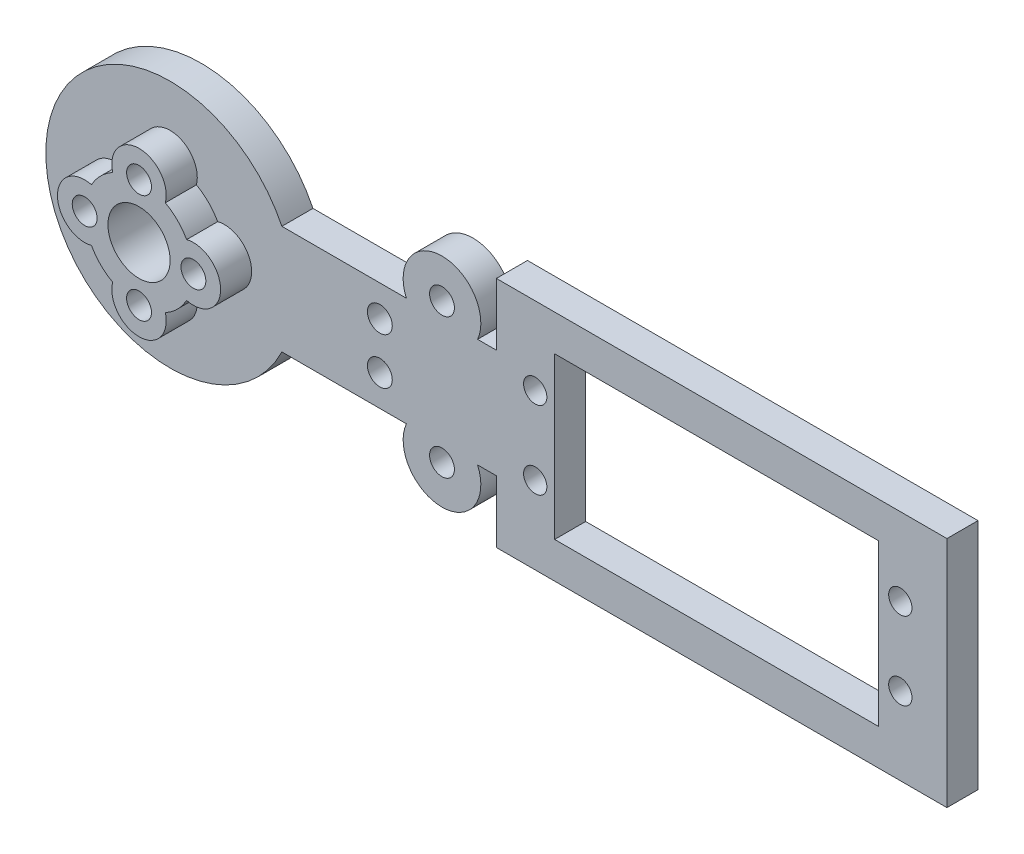
SolidWorks part; units mm, degrees
ref_plane "Front Plane" through (0, 0, 0) normal (0, 0, 1) x (1, 0, 0)
ref_plane "Top Plane" through (0, 0, 0) normal (0, 1, 0) x (1, 0, 0)
ref_plane "Right Plane" through (0, 0, 0) normal (1, 0, 0) x (0, 0, -1)
sketch "Main_web_profile" plane through (0, 0, 0) normal (0, 0, 1) x (1, 0, 0)
  line L1 (0, -7) -> (60, -7)
  line L2 (0, -7) -> (0, 7)
  line L3 (0, 7) -> (60, 7)
  line L4 (60, -7) -> (60, 7)
  dimension "D1" = 60
  dimension "D2" = 14
  dimension "D3" = 7
extrude "Main_web" add sketch "Main_web_profile" along normal blind 4
sketch "Shoulder_horn_flange_profile" plane through (0, 0, 0) normal (0, 0, 1) x (1, 0, 0)
  circle A0 centre (0, 0) radius 16
  dimension "D1" = 32
extrude "Shoulder_horn_flange" add sketch "Shoulder_horn_flange_profile" along normal blind 4
sketch "Elbow_servo_mount_profile" plane through (0, 0, 0) normal (0, 0, 1) x (1, 0, 0)
  line L1 (42, -14) -> (90, -14)
  line L2 (42, -14) -> (42, 14)
  line L3 (42, 14) -> (90, 14)
  line L4 (90, -14) -> (90, 14)
  dimension "D1" = 48
  dimension "D2" = 28
  dimension "D3" = 42
  dimension "D4" = 14
extrude "Elbow_servo_mount" add sketch "Elbow_servo_mount_profile" along normal blind 4
sketch "SG90_body_clearance_profile" plane through (0, 0, 0) normal (0, 0, 1) x (1, 0, 0)
  line L1 (53.6, -6.5) -> (77.4, -6.5)
  line L2 (53.6, -6.5) -> (53.6, 6.5)
  line L3 (53.6, 6.5) -> (77.4, 6.5)
  line L4 (77.4, -6.5) -> (77.4, 6.5)
  dimension "D1" = 23.8
  dimension "D2" = 13
  dimension "D3" = 53.6
  dimension "D4" = 6.5
extrude "SG90_body_clearance" cut sketch "SG90_body_clearance_profile" along normal through all from offset 5
sketch "Elbow_tab_fasteners_profile" plane through (0, 0, 0) normal (0, 0, 1) x (1, 0, 0)
  circle A0 centre (51, 0) radius 1.3
  circle A1 centre (80, 0) radius 1.3
  dimension "D1" = 2.6
  dimension "D2" = 2.6
  dimension "D3" = 51
  dimension "D4" = 80
extrude "Elbow_tab_fasteners" cut sketch "Elbow_tab_fasteners_profile" along normal through all from offset 50
sketch "Shoulder_center_screw_access_profile" plane through (0, 0, 0) normal (0, 0, 1) x (1, 0, 0)
  circle A0 centre (0, 0) radius 4
  dimension "D1" = 8
extrude "Shoulder_center_screw_access" cut sketch "Shoulder_center_screw_access_profile" along normal through all from offset 50
sketch "Cable_tie_holes_profile" plane through (0, 0, 0) normal (0, 0, 1) x (1, 0, 0)
  circle A0 centre (27, -3) radius 1.6
  circle A1 centre (27, 3) radius 1.6
  dimension "D1" = 3.2
  dimension "D2" = 3.2
  dimension "D3" = 27
  dimension "D4" = 3
  dimension "D5" = 3
extrude "Cable_tie_holes" cut sketch "Cable_tie_holes_profile" along normal through all from offset 50
sketch "Passive_lower_mount_boss_profile" plane through (0, 0, 0) normal (0, 0, 1) x (1, 0, 0)
  circle A0 centre (35, -9) radius 5
  dimension "D1" = 10
  dimension "D2" = 35
  dimension "D3" = 9
extrude "Passive_lower_mount_boss" add sketch "Passive_lower_mount_boss_profile" along normal blind 4
sketch "Passive_upper_mount_boss_profile" plane through (0, 0, 0) normal (0, 0, 1) x (1, 0, 0)
  circle A0 centre (35, 9) radius 5
  dimension "D1" = 10
  dimension "D2" = 35
  dimension "D3" = 9
extrude "Passive_upper_mount_boss" add sketch "Passive_upper_mount_boss_profile" along normal blind 4
sketch "Passive_cheek_standoffs_profile" plane through (0, 0, 0) normal (0, 0, 1) x (1, 0, 0)
  circle A0 centre (35, -9) radius 1.6
  circle A1 centre (35, 9) radius 1.6
  dimension "D1" = 3.2
  dimension "D2" = 3.2
  dimension "D3" = 35
  dimension "D4" = 9
  dimension "D5" = 9
extrude "Passive_cheek_standoffs" cut sketch "Passive_cheek_standoffs_profile" along normal through all from offset 50
sketch "Shoulder_dowel_support_hub_profile" plane through (0, 0, 0) normal (0, 0, 1) x (1, 0, 0)
  circle A0 centre (0, 0) radius 7
  circle A1 centre (0, 0) radius 4
  dimension "D1" = 14
  dimension "D2" = 8
extrude "Shoulder_dowel_support_hub" add sketch "Shoulder_dowel_support_hub_profile" along normal blind 4 from offset 4
sketch "Raised_M3_washer_seats_PCD14_profile" plane through (0, 0, 0) normal (0, 0, 1) x (1, 0, 0)
  circle A0 centre (7, 0) radius 3.5
  circle A1 centre (-7, 0) radius 3.5
  circle A2 centre (0, 7) radius 3.5
  circle A3 centre (0, -7) radius 3.5
  dimension "D1" = 7
  dimension "D2" = 7
  dimension "D3" = 7
  dimension "D4" = 7
  dimension "D5" = 7
  dimension "D6" = 7
  dimension "D7" = 7
  dimension "D8" = 7
extrude "Raised_M3_washer_seats_height8" add sketch "Raised_M3_washer_seats_PCD14_profile" along normal blind 4 from offset 4
sketch "Metal_horn_M3_clearance_PCD14_profile" plane through (0, 0, 0) normal (0, 0, 1) x (1, 0, 0)
  circle A0 centre (7, 0) radius 1.6
  circle A1 centre (-7, 0) radius 1.6
  circle A2 centre (0, 7) radius 1.6
  circle A3 centre (0, -7) radius 1.6
  dimension "D1" = 3.2
  dimension "D2" = 3.2
  dimension "D3" = 3.2
  dimension "D4" = 3.2
  dimension "D5" = 7
  dimension "D6" = 7
  dimension "D7" = 7
  dimension "D8" = 7
extrude "Metal_horn_M3_clearance_PCD14" cut sketch "Metal_horn_M3_clearance_PCD14_profile" along normal through all from offset 50
sketch "Restore_shoulder_sleeve_bore_profile" plane through (0, 0, 0) normal (0, 0, 1) x (1, 0, 0)
  circle A0 centre (0, 0) radius 4
  dimension "D1" = 8
extrude "Restore_shoulder_sleeve_bore" cut sketch "Restore_shoulder_sleeve_bore_profile" along normal through all from offset 50
fillet "Fillet1" radius 7.5 4 edges at (42, -14, 2) (90, -14, 2) (90, 14, 2) (42, 14, 2)
sketch "Larger_elbow_servo_mount_replaces_SG90_opening_profile" plane through (0, 0, 0) normal (0, 0, 1) x (1, 0, 0)
  line L1 (42, -15) -> (100, -15)
  line L2 (42, -15) -> (42, 15)
  line L3 (42, 15) -> (100, 15)
  line L4 (100, -15) -> (100, 15)
  dimension "D1" = 58
  dimension "D2" = 30
extrude "Larger_elbow_servo_mount_replaces_SG90_opening" add sketch "Larger_elbow_servo_mount_replaces_SG90_opening_profile" along normal blind 4
sketch "MG996R_elbow_body_clearance_profile" plane through (0, 0, 0) normal (0, 0, 1) x (1, 0, 0)
  line L1 (49.5, -10.35) -> (91.2, -10.35)
  line L2 (49.5, -10.35) -> (49.5, 10.35)
  line L3 (49.5, 10.35) -> (91.2, 10.35)
  line L4 (91.2, -10.35) -> (91.2, 10.35)
  dimension "D1" = 41.7
  dimension "D2" = 20.7
extrude "MG996R_elbow_body_clearance" cut sketch "MG996R_elbow_body_clearance_profile" along normal through all from offset 5
sketch "MG996R_elbow_tab_fasteners_profile" plane through (0, 0, 0) normal (0, 0, 1) x (1, 0, 0)
  circle A0 centre (47, -5) radius 1.5
  circle A1 centre (47, 5) radius 1.5
  circle A2 centre (94, -5) radius 1.5
  circle A3 centre (94, 5) radius 1.5
  dimension "D1" = 3
  dimension "D2" = 3
  dimension "D3" = 3
  dimension "D4" = 3
extrude "MG996R_elbow_tab_fasteners" cut sketch "MG996R_elbow_tab_fasteners_profile" along normal through all from offset 50
